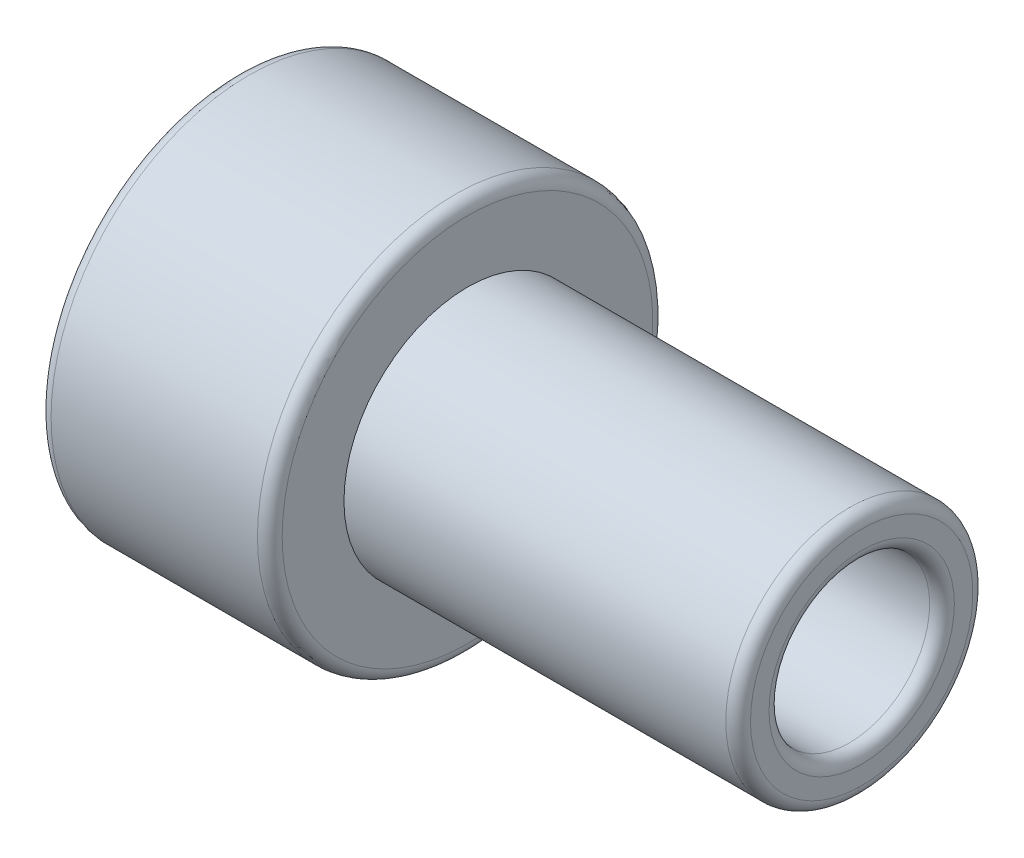
SolidWorks part; units mm, degrees
ref_plane "Front Plane" through (0, 0, 0) normal (0, 0, 1) x (1, 0, 0)
ref_plane "Top Plane" through (0, 0, 0) normal (0, 1, 0) x (1, 0, 0)
ref_plane "Right Plane" through (0, 0, 0) normal (1, 0, 0) x (0, 0, -1)
sketch "Sketch1" plane through (0, 0, 0) normal (0, 0, 1) x (1, 0, 0)
  line L0 (-1.1743, 0) -> (2.2457, 0) construction
  line L1 (11.3, 5) -> (-4.65, 5)
  line L2 (-4.65, 5) -> (-4.65, 8)
  line L3 (-4.65, 8) -> (-14, 8)
  line L4 (-14, 8) -> (-14, 0)
  line L5 (-14, 0) -> (11.3, 0)
  line L6 (11.3, 0) -> (11.3, 5)
  line L7 (4.65, 5.15) -> (4.65, 8)
  line L8 (4.65, 8) -> (14, 8)
  line L9 (14, 8) -> (14, 0)
  line L10 (14, 0) -> (11.5, 0)
  line L11 (11.5, 0) -> (11.5, 5.15)
  line L12 (11.5, 5.15) -> (4.65, 5.15)
  line L13 (-4.65, 8) -> (4.65, 8) construction
  line L14 (0, 0) -> (0, 8) construction
  dimension "D1" = 0.2
  dimension "D2" = 0.15
  dimension "D3" = 9.3
  dimension "D4" = 28
  dimension "D5" = 5
  dimension "D6" = 3
  dimension "D7" = 2.5
revolve "Revolve1" add sketch "Sketch1" angle 360 about L0
sketch "Sketch2" plane through (0, 0, 0) normal (1, 0, 0) x (0, 0, -1)
  circle A0 centre (0, 0) radius 3.25
  dimension "D1" = 6.5
extrude "Cut-Extrude1" cut sketch "Sketch2" against normal through all both and the other way through all
fillet "Fillet1" radius 0.5 5 edges at (11.3, 0, 5) (11.3, 0, -3.25) (-4.65, 0, 8) (-14, 0, -3.25) (-14, 0, 8)
